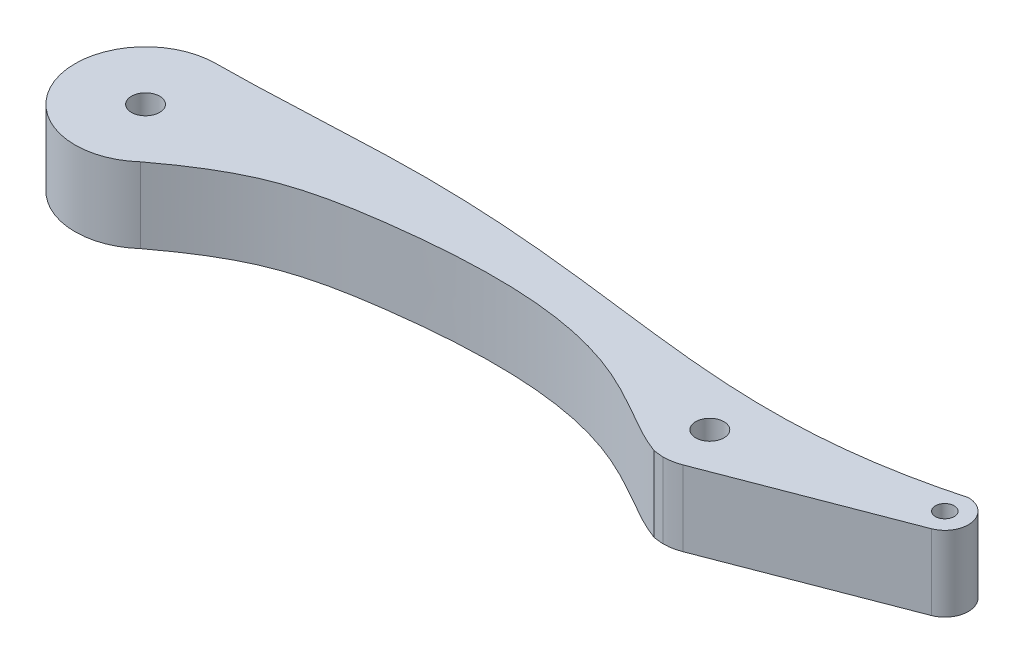
SolidWorks part; units mm, degrees
ref_plane "前视基准面" through (0, 0, 0) normal (0, 0, 1) x (1, 0, 0)
ref_plane "上视基准面" through (0, 0, 0) normal (0, 1, 0) x (1, 0, 0)
ref_plane "右视基准面" through (0, 0, 0) normal (1, 0, 0) x (0, 0, -1)
other "Configuration Table"
sketch "Sketch1" plane through (0, 0, 0) normal (0, 1, 0) x (1, 0, 0)
  line L0 (55, 0.0297) -> (60, 0.0297) construction
  line L1 (0, 7.5) -> (15, 6.8824)
  line L2 (79.3846, 7.4528) -> (80, 7.5297)
  line L3 (0, -7.5) -> (0.6313, -7.4734)
  line L4 (61.792, -4.6381) -> (80.896, 2.6958)
  line L5 (15, 0.0297) -> (4.0224, -6.3301) construction
  line L6 (15, 0.0297) -> (15, 8.0297) construction
  circle A0 centre (0, 0) radius 7.5
  circle A1 centre (60, 0.0297) radius 1.5
  circle A2 centre (60, 0.0297) radius 5
  circle A3 centre (80, 5.0297) radius 1
  circle A4 centre (80, 5.0297) radius 2.5
  spline S0 degree 3 poles (5.0373, -5.5566) (8.0216, -3.3229) (13.6358, 0.2367) (47.1128, 6.0862) (52.1284, -2.3765) (58.9707, -4.8632) knots 0.020667 0.020667 0.020667 0.020667 0.119806 0.217739 1 1 1 1
  spline S1 degree 3 poles (58.9707, -4.8632) (58.9781, -4.8632) (59.9926, -4.9703) (60, -4.9703) knots 0.714199 0.714199 0.714199 0.714199 0.714488 0.714488 0.714488 0.714488
  spline S2 degree 3 poles (0, 7.5) (6.5962, 7.5304) (41.0182, 10.2663) (57.4957, 1.4317) (80, 7.5297) knots 0 0 0 0 0.213971 1 1 1 1
  point P16 (15, 0.0297)
  dimension "D1" = 15
  dimension "D2" = 3
  dimension "D4" = 10
  dimension "D5" = 2
  dimension "D8" = 5
  dimension "D3" = 60
  dimension "D6" = 20
  dimension "D7" = 5
  dimension "D9" = 15
  dimension "D10" = 8
extrude "Boss-Extrude2" add sketch "Sketch1" along normal blind 8
sketch "Sketch2" plane through (0, 0, 0) normal (0, 1, 0) x (1, 0, 0)
  circle A0 centre (0, 0) radius 7.5
extrude "Boss-Extrude3" add sketch "Sketch2" along normal blind 8
sketch "Sketch3" plane through (0, 8, 0) normal (0, 1, 0) x (1, 0, 0)
  circle A0 centre (0, 0) radius 1.5
  dimension "D1" = 3
extrude "Cut-Extrude1" cut sketch "Sketch3" against normal through all
